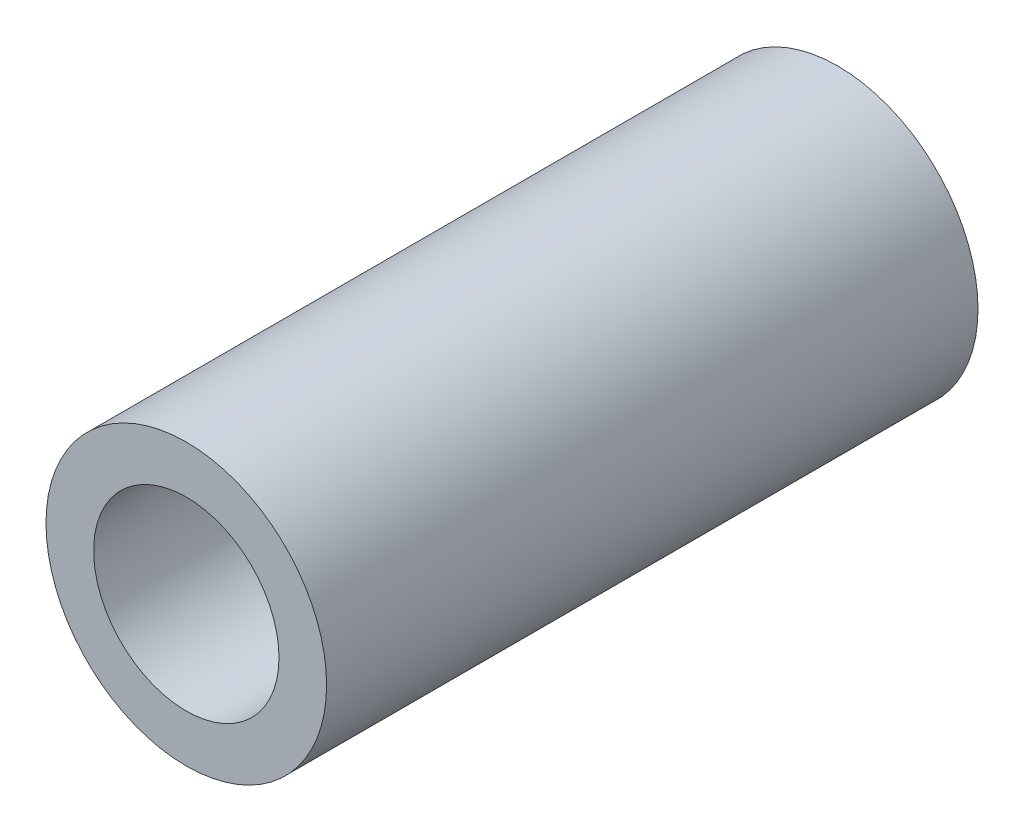
SolidWorks part; units mm, degrees
material "Paraffin_Wax"
ref_plane "Front Plane" through (0, 0, 0) normal (0, 0, 1) x (1, 0, 0)
ref_plane "Top Plane" through (0, 0, 0) normal (0, 1, 0) x (1, 0, 0)
ref_plane "Right Plane" through (0, 0, 0) normal (1, 0, 0) x (0, 0, -1)
sketch "Sketch1" plane through (0, 0, 0) normal (0, 0, 1) x (1, 0, 0)
  circle A0 centre (-23.7643, 16.8047) radius 14
sketch "Sketch2" plane through (0, 0, 0) normal (0, 0, 1) x (1, 0, 0)
  circle A0 centre (-23.7643, 16.8047) radius 9.25
extrude "Boss-Extrude3" add sketch "Sketch1" along normal blind 65 contours A0
extrude "Cut-Extrude1" cut sketch "Sketch2" along normal blind 65 contours A0
